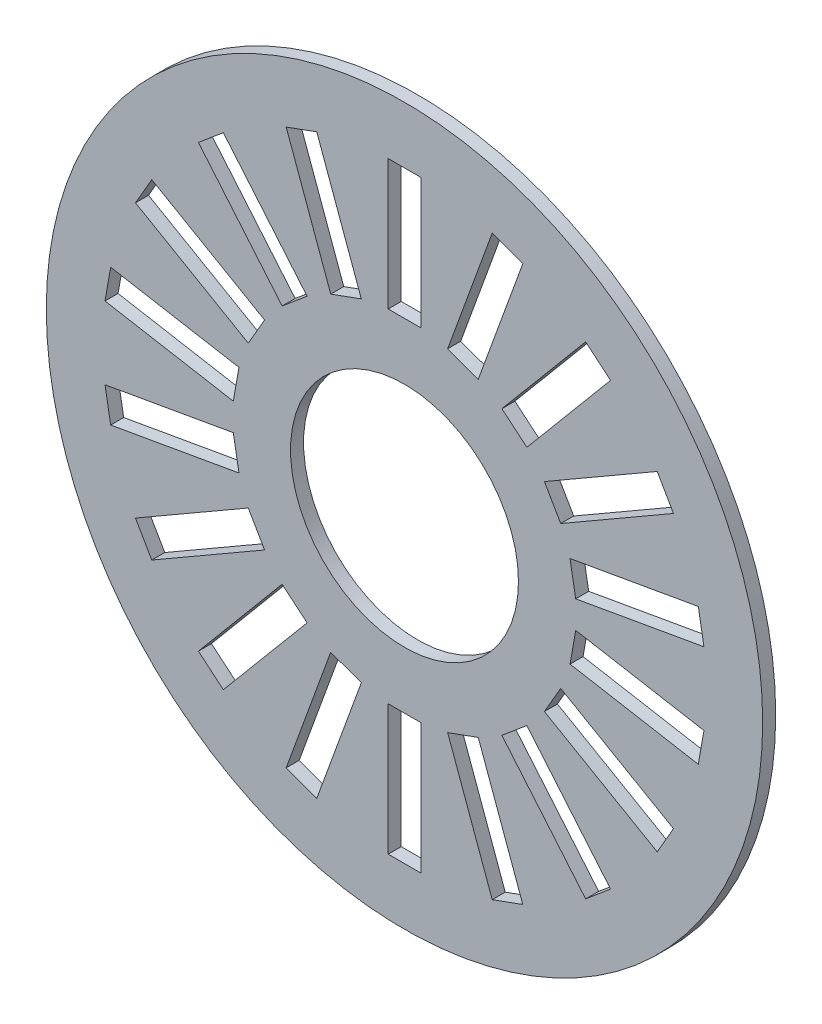
SolidWorks part; units mm, degrees
ref_plane "Plan de face" through (0, 0, 0) normal (0, 0, 1) x (1, 0, 0)
ref_plane "Plan de dessus" through (0, 0, 0) normal (0, 1, 0) x (1, 0, 0)
ref_plane "Plan de droite" through (0, 0, 0) normal (1, 0, 0) x (0, 0, -1)
sketch "Esquisse1" plane through (0, 0, 0) normal (0, 0, 1) x (1, 0, 0)
  circle A0 centre (0, 0) radius 3.5
  circle A1 centre (0, 0) radius 11
  dimension "D1" = 7
  dimension "D2" = 22
extrude "Boss.-Extru.1" add sketch "Esquisse1" along normal blind 0.4
sketch "Esquisse2" plane through (0, 0, 0.4) normal (0, 0, 1) x (1, 0, 0)
  line L0 (0, 3.5) -> (0, 11) construction
  line L2 (-0.5, 9.25) -> (0.5, 9.25)
  line L3 (-0.5, 9.25) -> (-0.5, 5.25)
  line L4 (-0.5, 5.25) -> (0.5, 5.25)
  line L5 (0.5, 9.25) -> (0.5, 5.25)
  line L6 (-0.5, 9.25) -> (0.5, 5.25) construction
  line L7 (-0.5, 5.25) -> (0.5, 9.25) construction
  circle A0 centre (0, 0) radius 3.5 construction
  circle A1 centre (0, 0) radius 11 construction
  point P7 (0, 7.25)
  dimension "D1" = 4
  dimension "D2" = 1
extrude "Enlèv. mat.-Extru.1" cut sketch "Esquisse2" against normal through all both and the other way through all
pattern_circular "Répétition circulaire1" count 18 every 20 about axis through (0, 0, 0) along (0, 0, 1) of "Enlèv. mat.-Extru.1"
